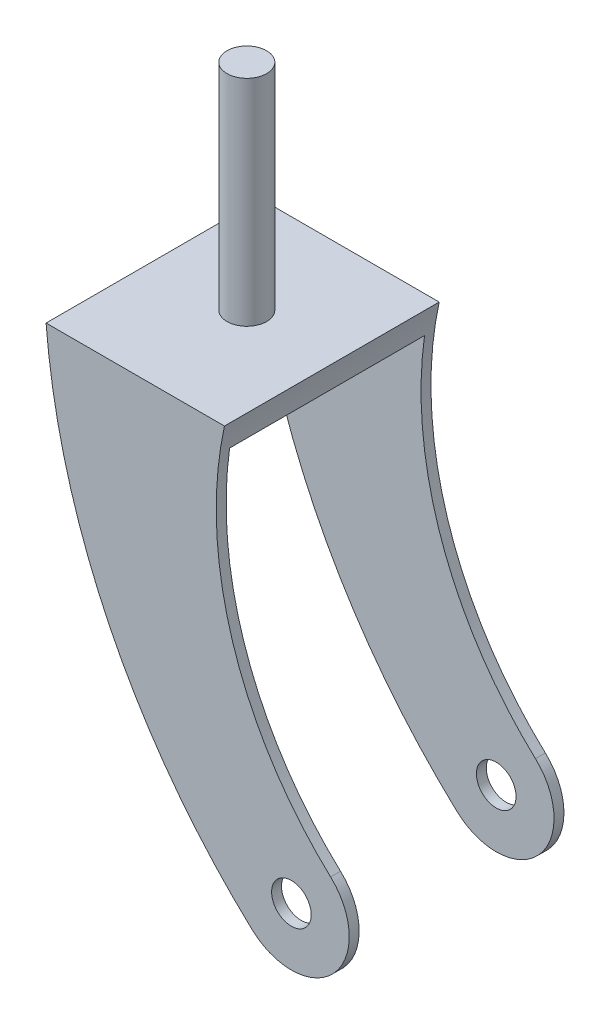
SolidWorks part; units mm, degrees
ref_plane "Alzado" through (0, 0, 0) normal (0, 0, 1) x (1, 0, 0)
ref_plane "Planta" through (0, 0, 0) normal (0, 1, 0) x (1, 0, 0)
ref_plane "Vista lateral" through (0, 0, 0) normal (1, 0, 0) x (0, 0, -1)
sketch "Croquis1" plane through (0, 0, 0) normal (0, 0, 1) x (1, 0, 0)
  line L0 (0, -5) -> (0, 110) construction
  line L1 (0, 110) -> (-74.2627, 110) construction
  line L2 (-74.2627, 110) -> (-20.2627, 110)
  line L3 (-11.8728, -17.8564) -> (11.8728, 7.8564) construction
  arc A0 (-74.2627, 110) -> (-11.8728, -17.8564) centre (121.1798, 126.2195) ccw
  arc A1 (-20.2627, 110) -> (11.8728, 7.8564) centre (84.9319, 86.9685) ccw
  arc A2 (-11.8728, -17.8564) -> (11.8728, 7.8564) centre (0, -5) ccw
  circle A3 centre (0, -5) radius 6
  circle A4 centre (0, -5) radius 75 construction
  dimension "D1" = 196.1144
  dimension "D2" = 107.6864
  dimension "D6" = 17.5
  dimension "D7" = 12
  dimension "D8" = 150
  dimension "D3" = 54
  dimension "D4" = 74.2627
  dimension "D5" = 115
extrude "Saliente-Extruir1" add sketch "Croquis1" along normal blind 65
sketch "Croquis2" plane through (0, 0, 0) normal (1, 0, 0) x (0, 0, -1)
  line L0 (-32.5, 110) -> (-32.5, -22.5) construction
  line L1 (-65, 110) -> (0, 110) construction
  line L2 (-65, -22.5) -> (0, -22.5) construction
  line L3 (-65, 110) -> (-65, 7.8564) construction
  line L4 (-62, -147) -> (-3, -147)
  line L5 (-62, -147) -> (-62, 102)
  line L6 (-62, 102) -> (-3, 102)
  line L7 (-3, -147) -> (-3, 102)
  line L8 (-62, -147) -> (-3, 102) construction
  line L9 (-62, 102) -> (-3, -147) construction
  line L10 (0, 7.8564) -> (0, 110) construction
  dimension "D1" = 3
  dimension "D2" = 3
  dimension "D3" = 8
extrude "Cortar-Extruir1" cut sketch "Croquis2" against normal through all both and the other way through all
sketch "Croquis3" plane through (0, 110, 0) normal (0, 1, 0) x (1, 0, 0)
  line L0 (-74.2627, -29.9696) -> (-20.2627, -32.5) construction
  line L1 (-74.2627, -65) -> (-74.2627, 0) construction
  line L2 (-20.2627, -65) -> (-20.2627, 0) construction
  circle A0 centre (-47.2627, -31.2348) radius 6
  dimension "D1" = 12
extrude "Saliente-Extruir2" add sketch "Croquis3" along normal blind 65
